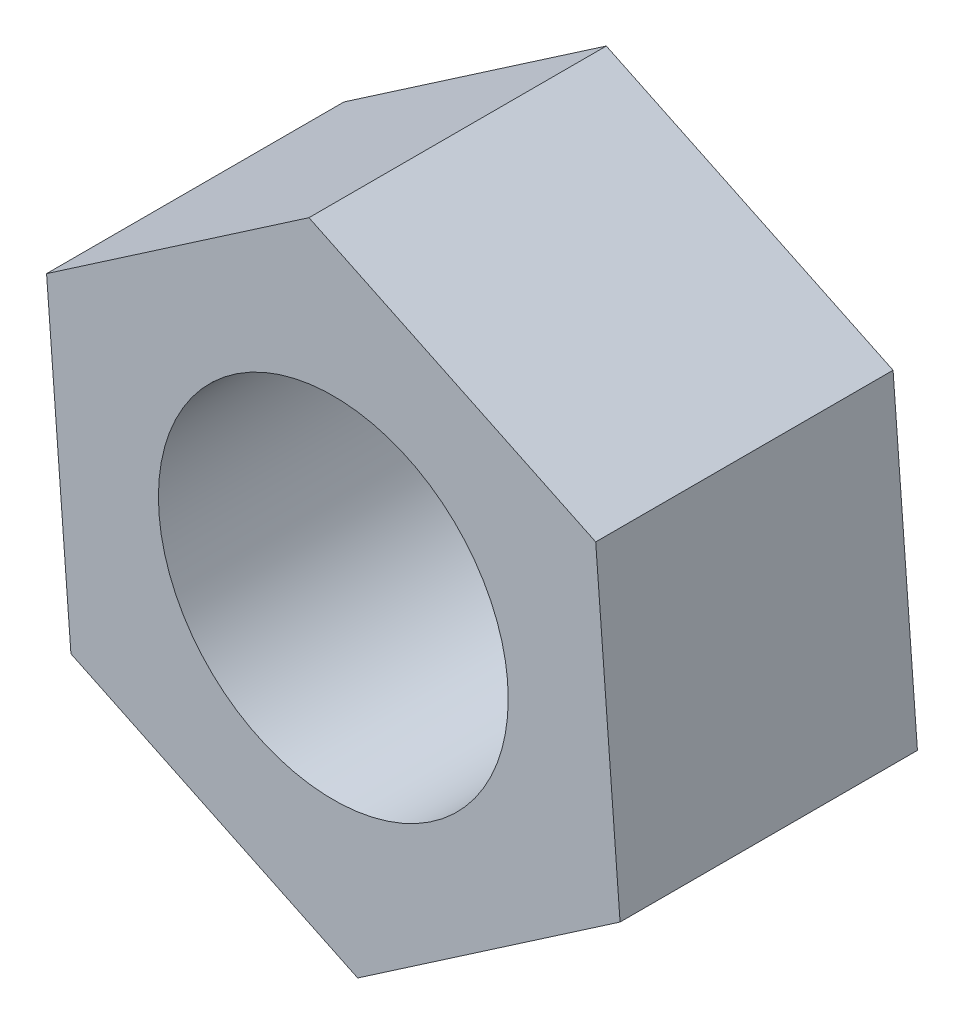
SolidWorks part; units mm, degrees
ref_plane "Front Plane" through (0, 0, 0) normal (0, 0, 1) x (1, 0, 0)
ref_plane "Top Plane" through (0, 0, 0) normal (0, 1, 0) x (1, 0, 0)
ref_plane "Right Plane" through (0, 0, 0) normal (1, 0, 0) x (0, 0, -1)
sketch "Sketch1" plane through (0, 0, 0) normal (0, 0, 1) x (1, 0, 0)
  line L1 (-0.5574, 7.25) -> (-6.5574, 3.1423)
  line L2 (-6.5574, 3.1423) -> (-6, -4.1077)
  line L3 (-6, -4.1077) -> (0.5574, -7.25)
  line L4 (0.5574, -7.25) -> (6.5574, -3.1423)
  line L5 (6.5574, -3.1423) -> (6, 4.1077)
  line L6 (6, 4.1077) -> (-0.5574, 7.25)
  circle A0 centre (0, 0) radius 6.2972 construction
  circle A1 centre (0, 0) radius 4
  dimension "D2" = 8
  dimension "D1" = 14.5
  dimension "D3" = 6
extrude "Boss-Extrude1" add sketch "Sketch1" along normal blind 6.8
